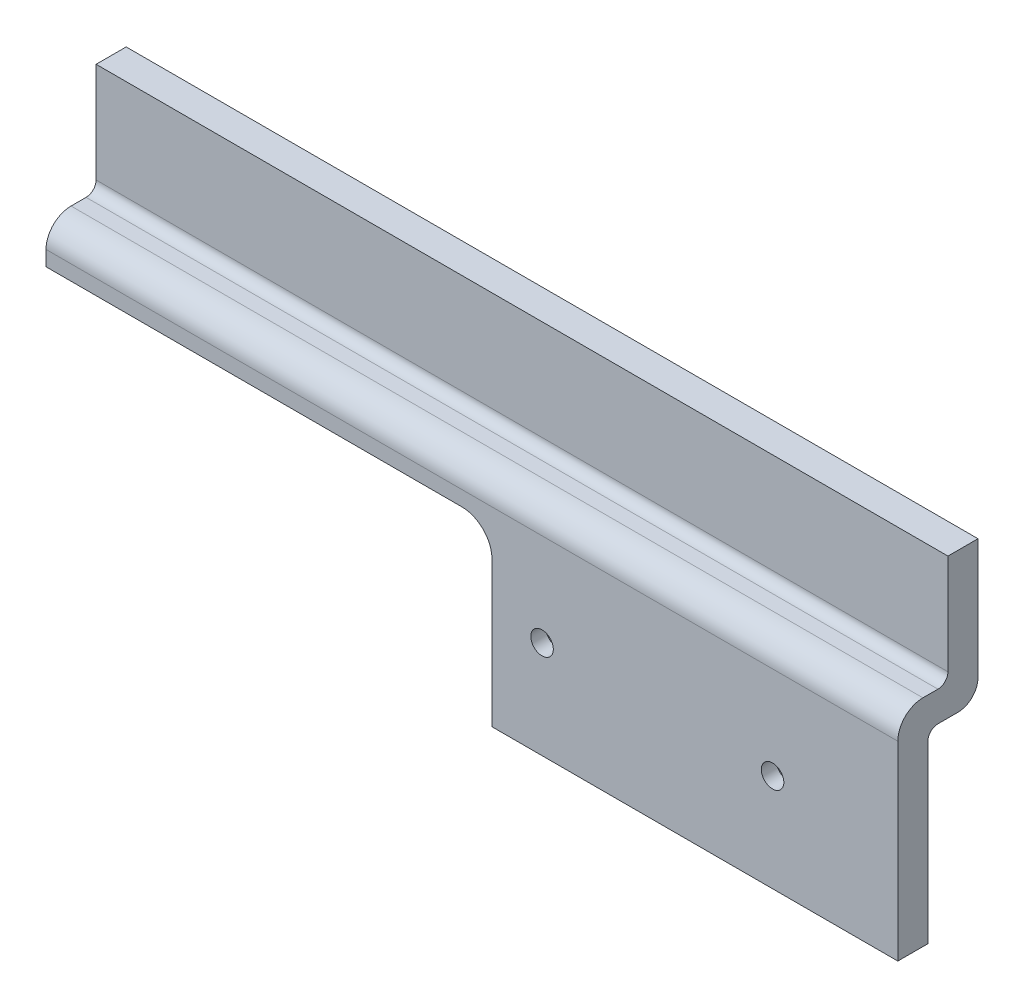
SolidWorks part; units mm, degrees
material "ABS"
ref_plane "Piano frontale" through (0, 0, 0) normal (0, 0, 1) x (1, 0, 0)
ref_plane "Piano superiore" through (0, 0, 0) normal (0, 1, 0) x (1, 0, 0)
ref_plane "Piano destro" through (0, 0, 0) normal (1, 0, 0) x (0, 0, -1)
sketch "Schizzo1" plane through (0, 0, 0) normal (1, 0, 0) x (0, 0, -1)
  line L0 (-6, 0) -> (0, 0)
  line L1 (0, 0) -> (0, 35)
  line L2 (-6, 0) -> (-6, 38)
  line L3 (-1, 43) -> (2, 43)
  line L4 (4, 45) -> (4, 65)
  line L5 (4, 65) -> (10, 65)
  line L6 (10, 65) -> (10, 41)
  line L7 (6, 37) -> (2, 37)
  arc A0 (-1, 43) -> (-6, 38) centre (-1, 38) ccw
  arc A1 (4, 45) -> (2, 43) centre (2, 45) cw
  arc A2 (2, 37) -> (0, 35) centre (2, 35) ccw
  arc A3 (10, 41) -> (6, 37) centre (6, 41) cw
  dimension "D7" = 5
  dimension "D8" = 2
  dimension "D9" = 4
  dimension "D1" = 6
  dimension "D2" = 43
  dimension "D3" = 37
  dimension "D4" = 16
  dimension "D5" = 6
  dimension "D6" = 28
extrude "Estrusione-Estrusione1" add sketch "Schizzo1" along normal blind 170
sketch "Schizzo3" plane through (0, 0, 0) normal (0, 0, -1) x (-1, 0, 0)
  line L0 (-145, 19.5) -> (-99, 19.5) construction
  line L2 (-170, 0) -> (-170, 35) construction
  point P0 (-145, 19.5)
  point P2 (-99, 19.5)
  dimension "D1" = 25
  dimension "D2" = 46
  dimension "D3" = 23.5
hole_wizard "Foro lamato per Bullone M5 a testa esagonale-2" positions "Schizzo3" profile "Schizzo4" counterbore size "M5" standard "ISO"
sketch "Schizzo4" plane through (145, 19.5, 0) normal (1, 0, 0) x (0, 1, 0)
  line L0 (0, 0) -> (0, 31.3519)
  line L1 (0, 31.3519) -> (2.25, 30)
  line L2 (2.25, 30) -> (2.25, 3)
  line L3 (2.25, 3) -> (5, 3)
  line L4 (5, 3) -> (5, 0)
  line L5 (5, 0) -> (0, 0)
  line L10 (0, 31.3519) -> (-2.25, 30) construction
  line L11 (0, -6.35) -> (0, 107.95) construction
  dimension "Hole Dia." = 4.5
  dimension "Hole Depth" = 30
  dimension "C'Bore Dia." = 10
  dimension "C'Bore Depth" = 3
  dimension "Drill Angle" = 118
sketch "Schizzo5" plane through (0, 0, 0) normal (0, 0, -1) x (-1, 0, 0)
  line L0 (-170, 0) -> (0, 0) construction
  line L1 (-89, 0) -> (0, 0)
  line L2 (-89, 0) -> (-89, 35)
  line L3 (-89, 35) -> (0, 35)
  line L4 (0, 0) -> (0, 35)
  line L5 (0, 0) -> (0, 35) construction
  circle A0 centre (-99, 19.5) radius 2.25 construction
  dimension "D2" = 10
  dimension "D1" = 35
extrude "Taglio-Estrusione1" cut sketch "Schizzo5" against normal blind 100
fillet "Raccordo1" radius 6 1 edges at (89, 35, 3)
